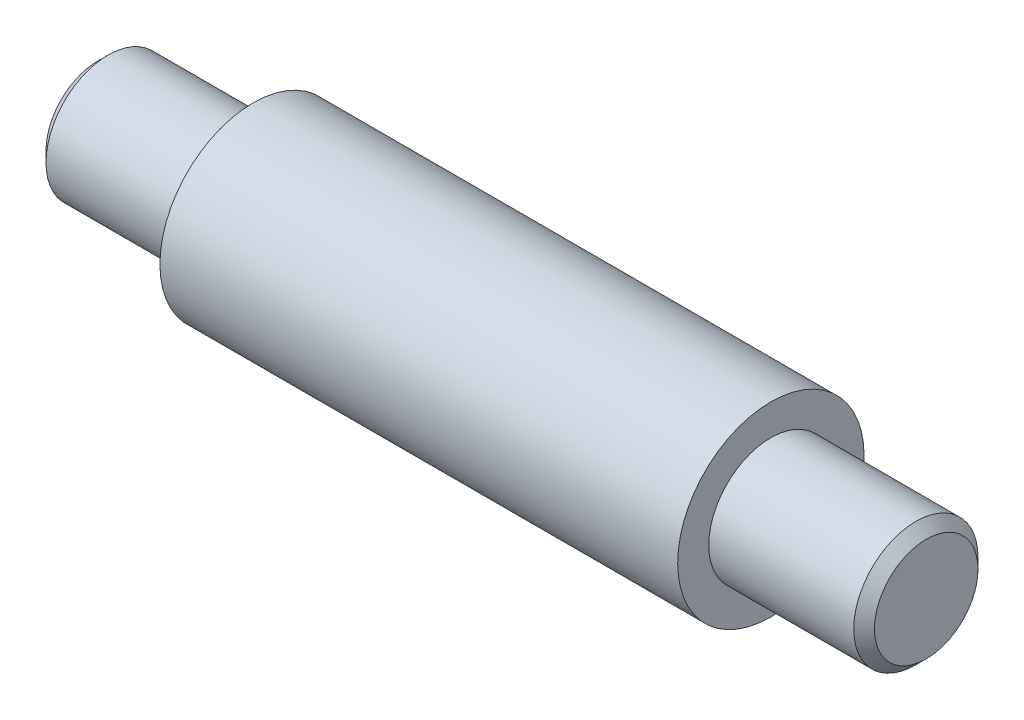
SolidWorks part; units mm, degrees
ref_plane "Front Plane" through (0, 0, 0) normal (0, 0, 1) x (1, 0, 0)
ref_plane "Top Plane" through (0, 0, 0) normal (0, 1, 0) x (1, 0, 0)
ref_plane "Right Plane" through (0, 0, 0) normal (1, 0, 0) x (0, 0, -1)
sketch "Sketch1" plane through (0, 0, 0) normal (0, 0, 1) x (1, 0, 0)
  line L0 (-40, 0) -> (40, 0)
  line L1 (-40, 0) -> (-40, 6)
  line L2 (-40, 6) -> (-25, 6)
  line L3 (-25, 6) -> (-25, 9)
  line L4 (-25, 9) -> (25, 9)
  line L5 (25, 9) -> (25, 6)
  line L6 (25, 6) -> (40, 6)
  line L7 (40, 6) -> (40, 0)
  point P0 (0, 0)
  dimension "D1" = 6
  dimension "D2" = 15
  dimension "D3" = 50
  dimension "D4" = 15
  dimension "D5" = 6
  dimension "D6" = 3
revolve "Revolve1" add sketch "Sketch1" angle 360 about L0
chamfer "Chamfer1" distance 1 angle 45 2 edges at (40, 0, 6) (-40, 0, 6)
